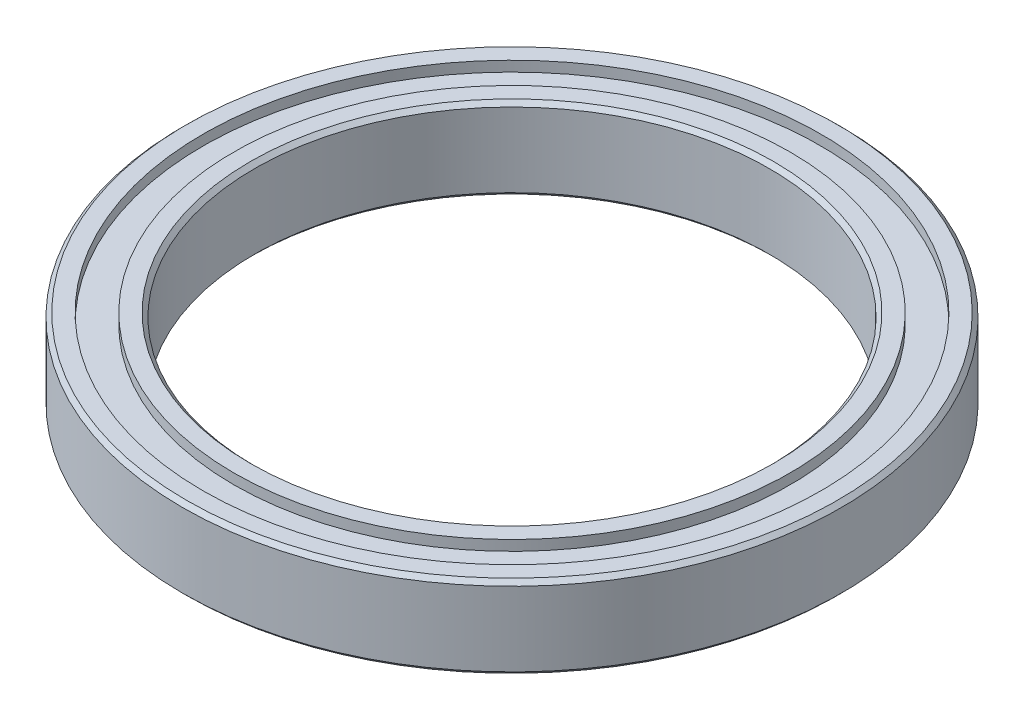
SolidWorks part; units mm, degrees
material "AISI 304"
ref_plane "前视基准面" through (0, 0, 0) normal (0, 0, 1) x (1, 0, 0)
ref_plane "上视基准面" through (0, 0, 0) normal (0, 1, 0) x (1, 0, 0)
ref_plane "右视基准面" through (0, 0, 0) normal (1, 0, 0) x (0, 0, -1)
sketch "草图1" plane through (0, 0, 0) normal (0, 1, 0) x (1, 0, 0)
  circle A0 centre (0, 0) radius 12.5
  circle A1 centre (0, 0) radius 16
  dimension "D1" = 25
  dimension "D2" = 32
extrude "凸台-拉伸1" add sketch "草图1" along normal blind 4
chamfer "倒角1" distance 0.2 angle 45 4 edges at (0, 0, 12.5) (0, 4, 16) (0, 0, 16) (0, 4, 12.5)
sketch "草图2" plane through (0, 4, 0) normal (0, 1, 0) x (1, 0, 0)
  circle A0 centre (0, 0) radius 13.5
  circle A1 centre (0, 0) radius 15
  dimension "D1" = 27
  dimension "D2" = 30
extrude "切除-拉伸1" cut sketch "草图2" against normal blind 0.5
sketch "草图3" plane through (0, 0, 0) normal (0, -1, 0) x (1, 0, 0)
  circle A0 centre (0, 0) radius 13.5
  circle A1 centre (0, 0) radius 15
  dimension "D1" = 27
  dimension "D2" = 30
extrude "切除-拉伸2" cut sketch "草图3" against normal blind 0.5
